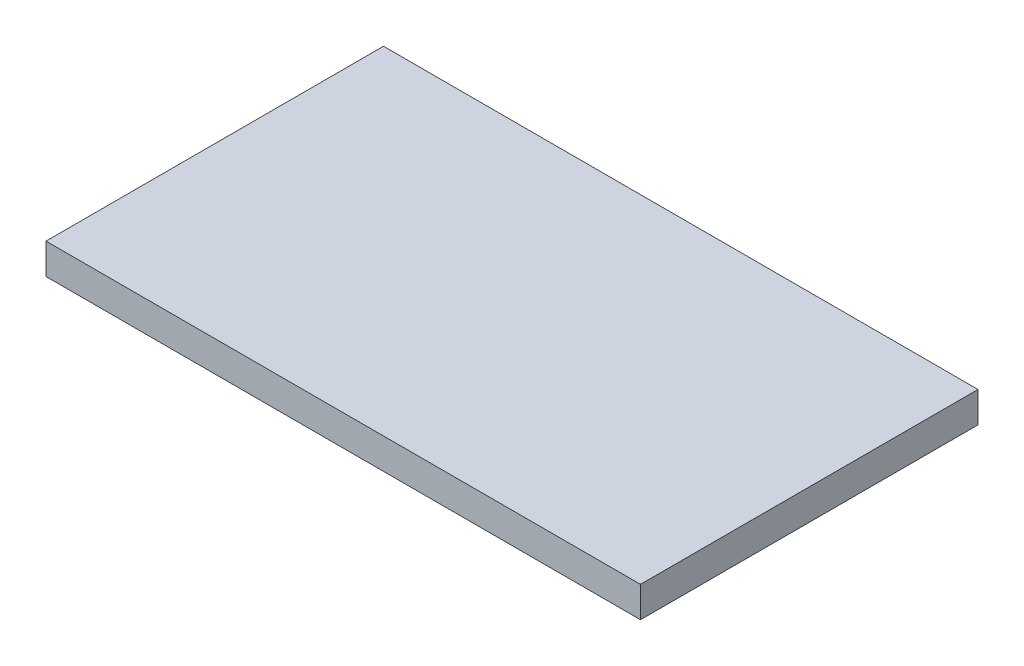
SolidWorks part; units mm, degrees
material "玻璃"
ref_plane "前视基准面" through (0, 0, 0) normal (0, 0, 1) x (1, 0, 0)
ref_plane "上视基准面" through (0, 0, 0) normal (0, 1, 0) x (1, 0, 0)
ref_plane "右视基准面" through (0, 0, 0) normal (1, 0, 0) x (0, 0, -1)
other "Configuration Table"
sketch "草图1" plane through (0, 0, 0) normal (0, 1, 0) x (1, 0, 0)
  line L1 (0, -55) -> (0, 55) construction
  line L2 (0, 8.8) -> (15.5, 8.8)
  line L3 (15.5, 8.8) -> (15.5, -8.8)
  line L4 (15.5, -8.8) -> (-15.5, -8.8)
  line L5 (-15.5, -8.8) -> (-15.5, 8.8)
  line L6 (-15.5, 8.8) -> (0, 8.8)
extrude "凸台-拉伸1" add sketch "草图1" along normal blind 1.6
